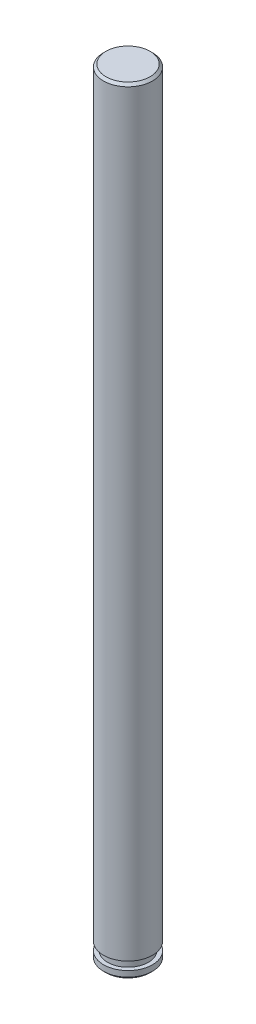
SolidWorks part; units mm, degrees
material "Custom Stainless Steel 1"
ref_plane "Front Plane" through (0, 0, 0) normal (0, 0, 1) x (1, 0, 0)
ref_plane "Top Plane" through (0, 0, 0) normal (0, 1, 0) x (1, 0, 0)
ref_plane "Right Plane" through (0, 0, 0) normal (1, 0, 0) x (0, 0, -1)
sketch "Sketch1" plane through (0, 0, 0) normal (0, 1, 0) x (1, 0, 0)
  circle A0 centre (0, 0) radius 1.5
  dimension "D1" = 3
extrude "Boss-Extrude1" add sketch "Sketch1" along normal blind 47.5
chamfer "Chamfer1" distance 0.15 angle 45 2 edges at (0, 47.5, 1.5) (0, 0, 1.5)
sketch "Sketch2" plane through (0, 0, 0) normal (0, -1, 0) x (1, 0, 0)
  circle A0 centre (0, 0) radius 1.5
  circle A1 centre (0, 0) radius 1.5 construction
  circle A2 centre (0, 0) radius 1.25
  dimension "D1" = 2.5
extrude "Cut-Extrude1" cut sketch "Sketch2" along normal blind 0.5 from surface
